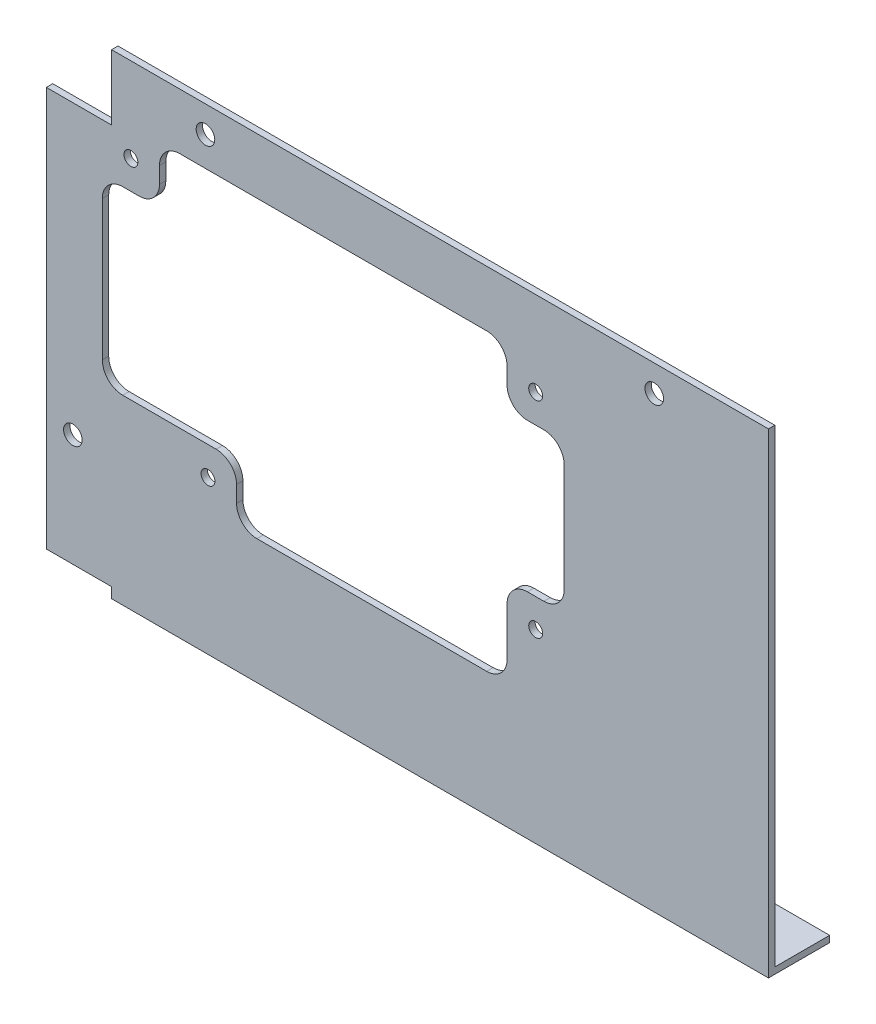
SolidWorks part; units mm, degrees
ref_plane "Front Plane" through (0, 0, 0) normal (0, 0, 1) x (1, 0, 0)
ref_plane "Top Plane" through (0, 0, 0) normal (0, 1, 0) x (1, 0, 0)
ref_plane "Right Plane" through (0, 0, 0) normal (1, 0, 0) x (0, 0, -1)
sketch "Sketch1" plane through (0, 0, 0) normal (0, 0, 1) x (1, 0, 0)
  line L1 (112.395, -73.025) -> (-112.395, -73.025)
  line L2 (112.395, -73.025) -> (112.395, 73.025)
  line L3 (112.395, 73.025) -> (-112.395, 73.025)
  line L4 (-112.395, -73.025) -> (-112.395, 73.025)
  line L5 (112.395, -73.025) -> (-112.395, 73.025) construction
  line L6 (112.395, 73.025) -> (-112.395, -73.025) construction
  point P0 (0, 0)
  dimension "D1" = 224.79
  dimension "D2" = 146.05
extrude "Boss-Extrude1" add sketch "Sketch1" along normal blind 1.9837
sketch "Sketch2" plane through (0, 0, 1.9837) normal (0, 0, 1) x (1, 0, 0)
  line L1 (-112.395, 73.025) -> (-92.075, 73.025)
  line L2 (-112.395, 73.025) -> (-112.395, 52.705)
  line L3 (-112.395, 52.705) -> (-92.075, 52.705)
  line L4 (-92.075, 73.025) -> (-92.075, 52.705)
  line L5 (-112.395, -73.025) -> (-92.075, -73.025)
  line L6 (-112.395, -73.025) -> (-112.395, -71.755)
  line L7 (-112.395, -71.755) -> (-92.075, -71.755)
  line L8 (-92.075, -73.025) -> (-92.075, -71.755)
  dimension "D1" = 20.32
  dimension "D2" = 20.32
  dimension "D3" = 1.27
extrude "Corner Cut" cut sketch "Sketch2" against normal through all
sketch "Sketch3" plane through (0, 0, 1.9837) normal (0, 0, 1) x (1, 0, 0)
  line L0 (-23.075, 46.705) -> (-23.075, 52.705) construction
  line L1 (-86.075, 46.705) -> (39.925, 46.705) construction
  line L2 (-86.075, 46.705) -> (-86.075, -27.295) construction
  line L3 (-86.075, -27.295) -> (39.925, -27.295) construction
  line L4 (39.925, 46.705) -> (39.925, -27.295) construction
  line L5 (-92.075, 52.705) -> (45.925, 52.705) construction
  line L6 (-92.075, 52.705) -> (-92.075, -33.295) construction
  line L7 (-92.075, -33.295) -> (45.925, -33.295) construction
  line L8 (45.925, 52.705) -> (45.925, -33.295) construction
  line L9 (-112.395, 52.705) -> (-112.395, -71.755) construction
  line L10 (-86.075, 9.705) -> (-92.075, 9.705) construction
  line L11 (112.395, 73.025) -> (-92.075, 73.025) construction
  circle A0 centre (-86.075, 46.705) radius 2.159
  circle A1 centre (-62.0776, -27.295) radius 2.159
  circle A2 centre (39.925, -17.295) radius 2.159
  circle A3 centre (39.925, 46.705) radius 2.159
  dimension "D4" = 4.318
  dimension "D1" = 6
  dimension "D5" = 20.32
  dimension "D6" = 138
  dimension "D7" = 86
  dimension "D8" = 20.32
  dimension "D2" = 29.9974
  dimension "D3" = 16
extrude "PS Mount Holes" cut sketch "Sketch3" against normal through all
sketch "Sketch4" plane through (0, 0, 1.9837) normal (0, 0, 1) x (1, 0, 0)
  line L0 (-77.185, 55.595) -> (31.035, 55.595)
  line L1 (31.035, 55.595) -> (31.035, 37.815)
  line L2 (31.035, 37.815) -> (48.815, 37.815)
  line L3 (48.815, 37.815) -> (48.815, -8.405)
  line L4 (48.815, -8.405) -> (31.035, -8.405)
  line L5 (31.035, -8.405) -> (31.035, -36.185)
  line L6 (31.035, -36.185) -> (-53.1876, -36.185)
  line L7 (-53.1876, -36.185) -> (-53.1876, -18.405)
  line L8 (-53.1876, -18.405) -> (-94.965, -18.405)
  line L9 (-94.965, -18.405) -> (-94.965, 37.815)
  line L10 (-94.965, 37.815) -> (-77.185, 37.815)
  line L11 (-77.185, 37.815) -> (-77.185, 55.595)
  line L12 (-86.075, 46.705) -> (-77.185, 46.705) construction
  line L13 (-86.075, 37.815) -> (-86.075, 46.705) construction
  line L14 (-62.0776, -27.295) -> (-62.0776, -18.405) construction
  line L15 (39.925, -17.295) -> (39.925, -8.405) construction
  line L16 (39.925, 46.705) -> (31.035, 46.705) construction
  line L17 (-62.0776, -27.295) -> (-53.1876, -27.295) construction
  dimension "D1" = 17.78
extrude "PS Cutout" cut sketch "Sketch4" against normal through all
fillet "Fillet11" radius 6.35 12 edges at (-94.965, -18.405, 0.9919) (-53.1876, -36.185, 0.9919) (-53.1876, -18.405, 0.9919) (31.035, -36.185, 0.9919) (31.035, -8.405, 0.9919) (48.815, -8.405, 0.9919) (48.815, 37.815, 0.9919) (31.035, 37.815, 0.9919) (31.035, 55.595, 0.9919) (-77.185, 55.595, 0.9919) (-94.965, 37.815, 0.9919) (-77.185, 37.815, 0.9919)
sketch "Sketch5" plane through (0, 0, 1.9837) normal (0, 0, 1) x (1, 0, 0)
  line L1 (-112.395, 52.705) -> (-112.395, -71.755) construction
  line L2 (-113.665, -36.83) -> (-94.615, -36.83) construction
  line L3 (-62.865, 55.245) -> (-62.865, 74.295) construction
  line L4 (112.395, 73.025) -> (-92.075, 73.025) construction
  line L5 (-62.865, 64.77) -> (76.835, 64.77) construction
  circle A0 centre (-62.865, 64.77) radius 2.8956
  circle A1 centre (76.835, 64.77) radius 2.8956
  circle A2 centre (-104.14, -36.83) radius 2.8956
  dimension "D8" = 5.7912
  dimension "D1" = 101.6
  dimension "D2" = 139.7
  dimension "D4" = 1.27
  dimension "D5" = 19.05
  dimension "D6" = 1.27
  dimension "D7" = 19.05
  dimension "D3" = 41.275
extrude "Frame-Mounts" cut sketch "Sketch5" against normal through all
sketch "Sketch8" plane through (0, -73.025, 0) normal (0, -1, 0) x (1, 0, 0)
  line L0 (112.395, 1.9837) -> (112.395, 0) construction
  line L1 (-92.075, 1.9837) -> (112.395, 1.9837)
  line L2 (-92.075, 1.9837) -> (-92.075, -17.0663)
  line L3 (-92.075, -17.0663) -> (112.395, -17.0663)
  line L4 (112.395, 1.9837) -> (112.395, -17.0663)
  dimension "D1" = 19.05
extrude "Boss-Extrude2" add sketch "Sketch8" along normal blind 1.9837
equation "\"Height\"= 32in"
equation "\"Width\"= 23in"
equation "\"Depth\"= 20in"
equation "\"Plexi\"= .121in"
equation "\"EBWidth\"= 9in"
equation "\"ComponentMountDia\"=0.1770"
equation "\"MagnetThickness\"=3mm"
equation "\"MagnetDiameter\"=12mm"
equation "\"DoorPlexi\"= \"Plexi\""
equation "\"ShelfThickness\"= .220in"
equation "\"BasePlateThickness\"= 0.5in"
equation "\"BasePlateWidth\"= \"Width\"+\"EBWidth\"-2*\"Plexi\""
equation "\"BasePlateDepth\"= \"Depth\"-\"Plexi\"-\"DoorPlexi\""
equation "\"Boxsize\"= .75in"
equation "\"BoxsizeHalf\"= \"Boxsize\"/2"
equation "\"Boxinner\"= .625in"
equation "\"CornerCube\"= 0.75in"
equation "\"FingerLength\"= 1.125in"
equation "\"FingerWidth\"= .625in"
equation "\"Cutwidth\"= .016in"
equation "\"Earsize\"= 1in + \"Cutwidth\" /2"
equation "\"Slotsize\"= 1in - \"Cutwidth\" / 2"
equation "\"InnerWidth\"= \"Width\" - 2* \"Plexi\""
equation "\"InnerHeight\"= \"Height\" -2 * \"Plexi\""
equation "\"InnerDepth\"= \"Depth\" - 2*\"Plexi\""
equation "\"FrontDoorGap\"= .1in"
equation "\"TopDepth\"= \"Depth\"-\"DoorPlexi\"-\"FrontDoorGap\""
equation "\"TopBarDepth\"= \"Depth\"-\"DoorPlexi\"-\"Plexi\"-2*\"MagnetThickness\"-2*\"CornerCube\""
equation "\"RearNumHoles\"= 7"
equation "\"RearHolesBorder\"= 2.2"
equation "\"RearHoleSpacing\"= (\"Width\" - 2*\"RearHolesBorder\") / (\"RearNumHoles\"-1)"
equation "\"RearBarLength\"= (\"InnerWidth\"-2*\"CornerCube\")"
equation "\"RearTopNumHoles\"= 6"
equation "\"RearTopHolesBorder\"= 2.5"
equation "\"RearTopHolesSpacing\"= (\"Width\" - 2*\"RearTopHolesBorder\") / (\"RearTopNumHoles\"-1)"
equation "\"SideTopNumHoles\"= 5"
equation "\"SideTopHoleOffset\"=\"CornerCube\"+\"FingerLength\"+\"Plexi\"+.5"
equation "\"SideTopHoleSpacing\"= (\"TopBarDepth\"-2*\"SideTopHoleOffset\") / (\"SideTopNumHoles\"-1)"
equation "\"SideHorizNumHoles\"= 6"
equation "\"SideHorizHoleBorder\"= 2.25"
equation "\"SideHorizHoleSpacing\"= (\"TopBarDepth\"-2*\"SideHorizHoleBorder\") / (\"SideHorizNumHoles\"-1)"
equation "\"SideVertBarLength\"=\"Height\"-\"BasePlateThickness\"-2*\"CornerCube\"-\"Plexi\""
equation "\"SideVertNumHoles\"= 6"
equation "\"SideVertHolesBorder\"= \"CornerCube\"+\"FingerLength\"+.9"
equation "\"SideVertHoleSpacing\"= (\"InnerHeight\" - 2*\"SideVertHolesBorder\") / (\"SideVertNumHoles\"-1)"
equation "\"RearSideVertNumHoles\"= 7"
equation "\"RearSideVertHolesBorder\"= 2.5"
equation "\"RearSideVertHoleSpacing\"= (\"InnerHeight\" - 2*\"RearSideVertHolesBorder\") / (\"RearSideVertNumHoles\"-1)"
equation "\"RivetDia\"= .228in"
equation "\"SlotDepth\"= \"Plexi\" + 0.75in + .005in"
equation "\"SideSlotWidth\"= \"Plexi\"+.005in"
equation "\"SidePanelVertSpacing\"= (\"Height\"-2*(1.75-\"Plexi\")) / 5"
equation "\"BottomPanelSideHoleSpacing\"= (\"InnerDepth\"-2*(1.75-\"Plexi\")) / 4"
equation "\"CoolerDepth\"= 11in"
equation "\"ShelfGap\"= 0.5in"
equation "\"ShelfDepth\"= \"TopBarDepth\"+\"CornerCube\"-\"CoolerDepth\""
equation "\"ShelfBarDepth\"=\"ShelfDepth\"-2*\"CornerCube\""
equation "\"ShelfWidth\"= \"EBWidth\"-\"ShelfGap\""
equation "\"ShelfBarWidth\"= \"EBWidth\"-\"Boxsize\""
equation "\"ShelfBarWidthShort\"= \"ShelfBarWidth\"-\"Boxsize\"-\"ShelfGap\""
equation "\"ShelfHeight1\"= 13in"
equation "\"ShelfHeight2\"= 24in"
equation "\"IntakeWidth\"=4in"
equation "\"IntakeHeight\"=2in"
equation "\"ExhaustWidth\"=4in"
equation "\"ExhaustHeight\"=2in"
equation "\"VentSpacing\"=7in"
equation "\"VentVertLocation\"=12in"
equation "\"AngleBracketLength\"=20mm"
equation "\"AngleBracketWidth\"=10mm"
equation "\"AngleBracketThickness\"=1.5mm"
equation "\"AngleBracketHolePos\"=15mm"
equation "\"AngleBracketHoleDia\"=\"RivetDia\""
equation "\"ShelfBarAngleHole\"=\"ShelfGap\"+\"Boxsize\"+\"AngleBracketHolePos\""
equation "\"D5@Sketch5\"=\"Boxsize\""
equation "\"D7@Sketch5\"=\"Boxsize\""
equation "\"D8@Sketch5\"=\"RivetDia\""
equation "\"D6@Sketch3\"=138mm"
